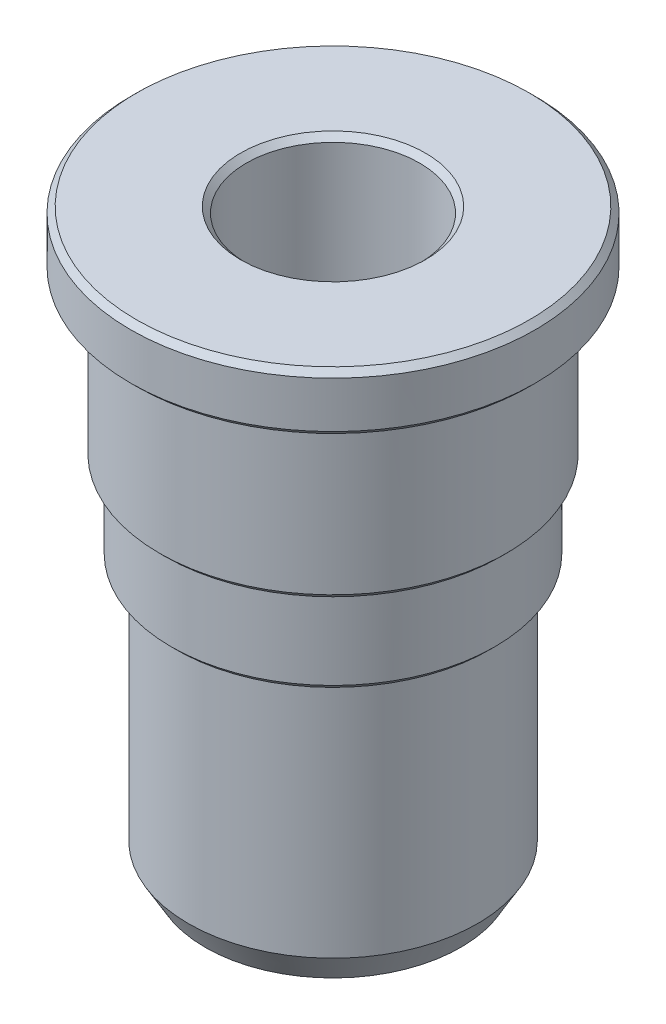
SolidWorks part; units mm, degrees
ref_plane "Płaszczyzna przednia" through (0, 0, 0) normal (0, 0, 1) x (1, 0, 0)
ref_plane "Płaszczyzna górna" through (0, 0, 0) normal (0, 1, 0) x (1, 0, 0)
ref_plane "Płaszczyzna prawa" through (0, 0, 0) normal (1, 0, 0) x (0, 0, -1)
sketch "Szkic1" plane through (0, 0, 0) normal (0, 0, 1) x (1, 0, 0)
  line L0 (0, 34.9454) -> (0, -82.3997) construction
  line L1 (-15, -70.098) -> (-15, 29.902)
  line L2 (-15, 29.902) -> (-35, 29.902)
  line L3 (-35, 29.902) -> (-35, 19.902)
  line L4 (-35, 19.902) -> (-30, 19.902)
  line L5 (-30, 19.902) -> (-30, -8.098)
  line L6 (-22.1132, -70.098) -> (-15, -70.098)
  line L7 (-30, -8.098) -> (-28, -8.098)
  line L8 (-28, -8.098) -> (-28, -23.098)
  line L9 (-28, -23.098) -> (-25, -23.098)
  line L10 (-25, -23.098) -> (-25, -65.098)
  line L11 (-25, -65.098) -> (-22.1132, -70.098)
  dimension "D1" = 30
  dimension "D2" = 60
  dimension "D3" = 10
  dimension "D4" = 70
  dimension "D5" = 56
  dimension "D6" = 28
  dimension "D7" = 15
  dimension "D8" = 100
  dimension "D9" = 50
  dimension "D10" = 30
  dimension "D11" = 5
revolve "Obrót1" add sketch "Szkic1" angle 360 about L0
chamfer "Sfazowanie1" distance 1 angle 45 6 edges at (0, 29.902, 15) (0, 29.902, 35) (0, -23.098, 28) (0, -8.098, 30) (0, -70.098, 15) (0, 19.902, 35)
